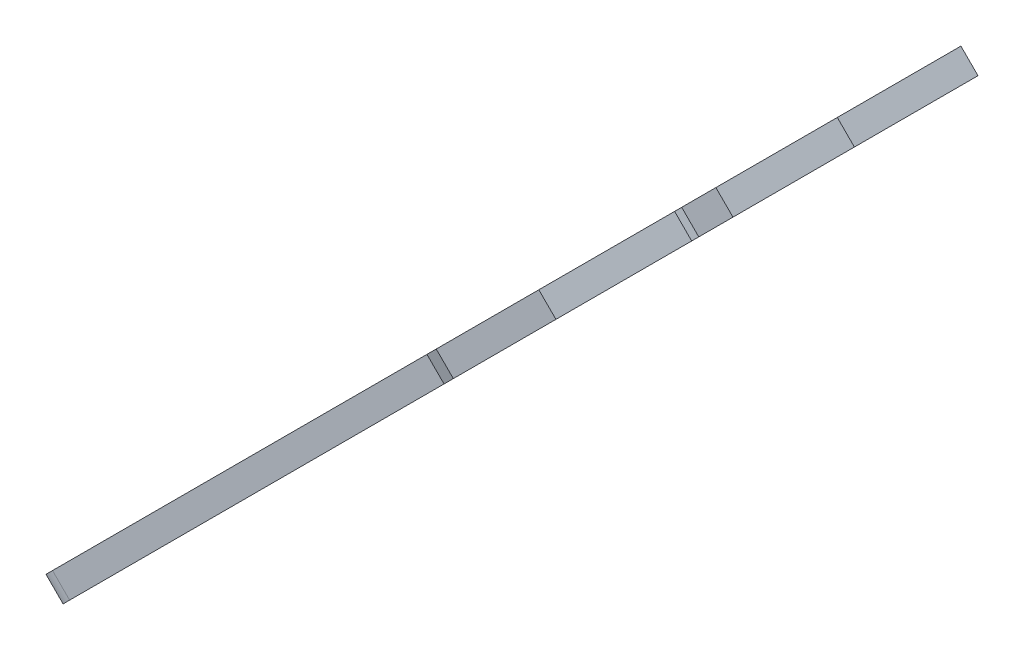
SolidWorks part; units mm, degrees
ref_plane "Front Plane" through (0, 0, 0) normal (0, 0, 1) x (1, 0, 0)
ref_plane "Top Plane" through (0, 0, 0) normal (0, 1, 0) x (1, 0, 0)
ref_plane "Right Plane" through (0, 0, 0) normal (1, 0, 0) x (0, 0, -1)
sketch "Sketch1" plane through (0, 0, 0) normal (0, 0, 1) x (1, 0, 0)
  line L0 (-4.4901, -21.951) -> (0, -26.4411)
  line L1 (-4.4901, -21.951) -> (-143.9339, -161.3948)
  line L2 (0, -26.4411) -> (-139.4438, -165.8849)
  line L3 (-143.9339, -161.3948) -> (-139.4438, -165.8849)
  line L4 (-143.6841, -161.1449) -> (-136.1856, -153.6464) construction
  line L5 (0, -17.4608) -> (9.1823, -26.6431) construction
  arc A0 (-208.1777, -57.2265) -> (-143.6841, -161.1449) centre (0, 0) ccw construction
  dimension "D1" = 6.35
  dimension "D2" = 6.35
extrude "Base Extrusion" add sketch "Sketch1" against normal up to surface (88.9 mm away) and the other way offset from surface (15.5875 mm away) 12.7
sketch "Sketch2" plane through (0, 0, -88.9) normal (0, 0, -1) x (-1, 0, 0)
  line L0 (12.3479, -38.7889) -> (16.838, -34.2988)
  line L1 (12.3479, -38.7889) -> (23.5732, -50.0143)
  line L2 (16.838, -34.2988) -> (28.0633, -45.5241)
  line L3 (23.5732, -50.0143) -> (28.0633, -45.5241)
  line L4 (0, -26.4411) -> (139.4438, -165.8849) construction
  line L5 (48.2689, -2.8679) -> (12.3479, -38.7889) construction
  line L6 (143.9339, -161.3948) -> (4.4901, -21.951) construction
  line L7 (59.4942, -14.0932) -> (23.5732, -50.0143) construction
extrude "Picker Clearance" cut sketch "Sketch2" against normal offset from surface (98.425 mm away) 9.525
sketch "Sketch3" plane through (13.2205, -13.2205, 0) normal (0.7071, -0.7071, 0) x (0, 0, -1)
  line L0 (88.9, -215.9) -> (-15.5875, -215.9) construction
  line L1 (54.2625, -203.2) -> (47.9125, -203.2)
  line L2 (54.2625, -203.2) -> (54.2625, -215.9)
  line L3 (54.2625, -215.9) -> (47.9125, -215.9)
  line L4 (47.9125, -203.2) -> (47.9125, -215.9)
  line L7 (-28.2875, 207.3747) -> (-28.2875, -207.3747) construction
  dimension "D1" = 12.7
  dimension "D2" = 76.2
  dimension "D3" = 6.35
extrude "Clothes Line Notch" cut sketch "Sketch3" against normal through all
sketch "Sketch4" plane through (0, 0, -88.9) normal (0, 0, -1) x (-1, 0, 0)
  line L0 (123.6156, -150.0567) -> (128.1057, -145.5666)
  line L1 (23.5732, -50.0143) -> (139.4438, -165.8849) construction
  line L2 (143.9339, -161.3948) -> (28.0633, -45.5241) construction
  line L3 (128.1057, -145.5666) -> (110.1452, -127.6061)
  line L4 (110.1452, -127.6061) -> (105.6551, -132.0962)
  line L5 (105.6551, -132.0962) -> (123.6156, -150.0567)
  dimension "D1" = 25.4
extrude "Tab to Top Plate" add sketch "Sketch4" along normal blind 6.35
pattern_linear "Top Plate Tabs" count 3 spacing 38.1 along (0.7071, 0.7071, 0) of "Tab to Top Plate"
sketch "Sketch5" plane through (8.7304, -8.7304, 0) normal (-0.7071, 0.7071, 0) x (0, 0, 1)
  line L1 (-6.35, -190.1467) -> (0, -190.1467)
  line L2 (-6.35, -190.1467) -> (-6.35, -164.7384)
  line L3 (-6.35, -164.7384) -> (0, -164.7384)
  line L4 (0, -190.1467) -> (0, -164.7384)
  dimension "D1" = 25.4083
  dimension "D2" = 6.35
extrude "Base Plate Tab" cut sketch "Sketch5" against normal blind 6.35
pattern_linear "Base Plate Tab holes" count 3 spacing 38.1 along (0.7071, 0.7071, 0) of "Base Plate Tab"
ref_plane "Plane1" through (-143.9339, -161.3948, -54.2625) normal (0, 0, 1) x (1, 0, 0)
sketch "Sketch8" plane through (8.7304, -8.7304, 0) normal (-0.7071, 0.7071, 0) x (0, 0, 1)
  line L0 (-88.9, -215.9) -> (-54.2625, -215.9) construction
  line L1 (-19.05, -209.55) -> (-6.35, -209.55)
  line L2 (-19.05, -209.55) -> (-19.05, -203.2)
  line L3 (-19.05, -203.2) -> (-6.35, -203.2)
  line L4 (-6.35, -209.55) -> (-6.35, -203.2)
  line L6 (15.5875, -18.6967) -> (15.5875, -215.9) construction
  dimension "D1" = 6.35
  dimension "D2" = 12.7
  dimension "D3" = 6.35
  dimension "D4" = 21.9375
extrude "Break Beam " cut sketch "Sketch8" against normal blind 6.35
pattern_linear "Break Beam Holes" count 2 spacing 19.05 along (0, 0, -1) of "Break Beam "
sketch "Sketch10" plane through (13.2205, -13.2205, 0) normal (0.7071, -0.7071, 0) x (0, 0, -1)
  line L0 (54.2625, -188.002) -> (47.9125, -192.2692) construction
  line L1 (47.9125, -188.002) -> (54.2625, -192.2692) construction
  circle A0 centre (51.0875, -190.1356) radius 2.0955
  dimension "D1" = 4.191
extrude "Clothes Line Hole" cut sketch "Sketch10" against normal through all
sketch "Sketch11" plane through (8.7304, -8.7304, 0) normal (-0.7071, 0.7071, 0) x (0.7071, 0.7071, 0)
  line L0 (-161.7656, 78.1771) -> (-161.7656, 120.5388) construction
  line L1 (-71.9749, 62.1718) -> (-71.9749, 114.782) construction
  line L2 (-27.4279, 73.0991) -> (-27.4279, 108.5444) construction
  line L5 (-52.0342, -9.525) -> (-52.0342, 88.9) construction
  line L6 (-91.9156, 95.25) -> (-91.9156, 88.9) construction
  line L7 (-36.1592, -9.525) -> (-36.1592, 88.9) construction
  line L8 (-18.6967, 88.9) -> (-18.6967, -15.5875) construction
  line L9 (-215.0889, 88.9) -> (-193.5156, 88.9) construction
  line L10 (-91.9156, 88.9) -> (-52.0342, 88.9) construction
  line L11 (-36.1592, 88.9) -> (-18.6967, 88.9) construction
  line L12 (-168.1156, 95.25) -> (-168.1156, 88.9) construction
  line L13 (-155.4156, 95.25) -> (-155.4156, 88.9) construction
  line B0 (-159.632, 88.9) -> (-163.8992, 88.9)
  line B1 (-163.8992, 76.962) -> (-166.2106, 76.962)
  line B2 (-166.2106, 76.962) -> (-166.2106, 80.137)
  line B3 (-166.2106, 80.137) -> (-163.8992, 80.137)
  line B4 (-163.8992, 80.137) -> (-163.8992, 88.9)
  line B5 (-163.8992, 76.962) -> (-163.8992, 73.66)
  line B6 (-163.8992, 73.66) -> (-159.632, 73.66)
  line B7 (-159.632, 76.962) -> (-159.632, 73.66)
  line B8 (-159.632, 80.137) -> (-159.632, 88.9)
  line B9 (-157.3206, 80.137) -> (-159.632, 80.137)
  line B10 (-157.3206, 76.962) -> (-157.3206, 80.137)
  line B11 (-159.632, 76.962) -> (-157.3206, 76.962)
  line B12 (-69.8413, 88.9) -> (-74.1085, 88.9)
  line B13 (-74.1085, 76.962) -> (-76.4199, 76.962)
  line B14 (-76.4199, 76.962) -> (-76.4199, 80.137)
  line B15 (-76.4199, 80.137) -> (-74.1085, 80.137)
  line B16 (-74.1085, 80.137) -> (-74.1085, 88.9)
  line B17 (-74.1085, 76.962) -> (-74.1085, 73.66)
  line B18 (-74.1085, 73.66) -> (-69.8413, 73.66)
  line B19 (-69.8413, 76.962) -> (-69.8413, 73.66)
  line B20 (-69.8413, 80.137) -> (-69.8413, 88.9)
  line B21 (-67.5299, 80.137) -> (-69.8413, 80.137)
  line B22 (-67.5299, 76.962) -> (-67.5299, 80.137)
  line B23 (-69.8413, 76.962) -> (-67.5299, 76.962)
  line B24 (-25.2943, 88.9) -> (-29.5615, 88.9)
  line B25 (-29.5615, 76.962) -> (-31.8729, 76.962)
  line B26 (-31.8729, 76.962) -> (-31.8729, 80.137)
  line B27 (-31.8729, 80.137) -> (-29.5615, 80.137)
  line B28 (-29.5615, 80.137) -> (-29.5615, 88.9)
  line B29 (-29.5615, 76.962) -> (-29.5615, 73.66)
  line B30 (-29.5615, 73.66) -> (-25.2943, 73.66)
  line B31 (-25.2943, 76.962) -> (-25.2943, 73.66)
  line B32 (-25.2943, 80.137) -> (-25.2943, 88.9)
  line B33 (-22.9829, 80.137) -> (-25.2943, 80.137)
  line B34 (-22.9829, 76.962) -> (-22.9829, 80.137)
  line B35 (-25.2943, 76.962) -> (-22.9829, 76.962)
sketch_block_instance "TSlot-1"
sketch_block "TSlot" parameters "D1"=3.302, "D2"=3.175
sketch_block_instance "TSlot-2"
sketch_block_instance "TSlot-3"
extrude "Chassis top Plate T Slot Hotes" cut sketch "Sketch11" against normal through all
sketch "Sketch12" plane through (8.7304, -8.7304, 0) normal (-0.7071, 0.7071, 0) x (0.7071, 0.7071, 0)
  line L0 (-204.9422, 0) -> (-200.7512, 6.35) construction
  line L1 (-200.7512, 0) -> (-204.9422, 6.35) construction
  line L2 (-209.55, 6.35) -> (-203.2, 6.35) construction
  line L3 (-204.9422, 0) -> (-204.9422, 6.35) construction
  line L4 (-72.3859, 0) -> (-68.1949, 6.35) construction
  line L5 (-68.1949, 0) -> (-72.3859, 6.35) construction
  line L6 (-29.5234, 0) -> (-25.3324, 6.35) construction
  line L7 (-25.3324, 0) -> (-29.5234, 6.35) construction
  circle A0 centre (-202.8467, 3.175) radius 2.0955
  circle A1 centre (-70.2904, 3.175) radius 2.0955
  circle A2 centre (-27.4279, 3.175) radius 2.0955
  dimension "D1" = 4.191
extrude "Chassis Base Plate Holes" cut sketch "Sketch12" against normal through all
fillet "V Funnel Corner Fillet" radius 7.62 1 edges at (-141.6889, -163.6398, 15.5875)
sketch "Sketch13" plane through (8.7304, -8.7304, 0) normal (-0.7071, 0.7071, 0) x (0, 0, 1)
  line L0 (15.5875, -18.6967) -> (15.5875, -208.28) construction
  line L2 (15.5875, -56.7967) -> (15.5875, -31.3967)
  line L4 (21.9375, -56.7967) -> (21.9375, -31.3967)
  line L5 (9.525, -44.0967) -> (15.5875, -44.0967) construction
  line L6 (9.525, -36.1592) -> (9.525, -52.0342) construction
  line L7 (21.9375, -56.7967) -> (15.5875, -69.228)
  line L8 (15.5875, -69.228) -> (15.5875, -56.7967)
  line L11 (21.9375, -31.3967) -> (21.9375, -18.6967)
  line L12 (21.9375, -18.6967) -> (15.5875, -18.6967)
  line L13 (15.5875, -31.3967) -> (15.5875, -18.6967)
  dimension "D1" = 25.4
  dimension "D2" = 6.35
extrude "Boss-Extrude1" add sketch "Sketch13" against normal blind 6.35
sketch "Sketch14" plane through (8.7304, -8.7304, 0) normal (-0.7071, 0.7071, 0) x (0, 0, 1)
  line L0 (9.525, -52.0342) -> (9.525, -36.1592)
  line L2 (9.525, -52.0342) -> (15.875, -52.0342)
  line L4 (9.525, -36.1592) -> (15.875, -36.1592)
  line L5 (15.875, -52.0342) -> (15.875, -36.1592)
  dimension "D1" = 6.35
extrude "Cut-Extrude1" cut sketch "Sketch14" against normal through all
sketch "Sketch16" plane through (-13.2205, -13.2205, 0) normal (0.7071, 0.7071, 0) x (0, 0, -1)
  line L0 (-21.9375, -18.6967) -> (15.0083, -18.6967) construction
  line L1 (88.9, -18.6967) -> (-21.9375, -18.6967) construction
  line L2 (15.0083, -18.6967) -> (51.9542, -18.6967) construction
  line L3 (51.9542, -18.6967) -> (88.9, -18.6967) construction
  line L4 (88.9, -12.3467) -> (-21.9375, -12.3467) construction
  line L5 (15.0083, -18.6967) -> (51.9542, -18.6967)
  line L6 (15.0083, -18.6967) -> (15.0083, -12.3467)
  line L7 (15.0083, -12.3467) -> (51.9542, -12.3467)
  line L8 (51.9542, -18.6967) -> (51.9542, -12.3467)
extrude "Boss-Extrude2" add sketch "Sketch16" along normal blind 6.35
sketch "Sketch17" [suppressed] plane through (-13.2205, -13.2205, 0) normal (0.7071, 0.7071, 0) x (0, 0, -1)
  line L0 (-21.9375, -18.6967) -> (15.0083, -18.6967) construction
  line L1 (88.9, -18.6967) -> (-21.9375, -18.6967) construction
  line L2 (15.0083, -18.6967) -> (51.9542, -18.6967) construction
  line L3 (51.9542, -18.6967) -> (88.9, -18.6967) construction
  line L4 (88.9, -12.3467) -> (-21.9375, -12.3467) construction
  line L5 (-21.9375, -18.6967) -> (15.0083, -18.6967)
  line L6 (-21.9375, -18.6967) -> (-21.9375, -12.3467)
  line L7 (-21.9375, -12.3467) -> (15.0083, -12.3467)
  line L8 (15.0083, -18.6967) -> (15.0083, -12.3467)
  line L10 (51.9542, -18.6967) -> (88.9, -18.6967)
  line L11 (51.9542, -18.6967) -> (51.9542, -12.3467)
  line L12 (51.9542, -12.3467) -> (88.9, -12.3467)
  line L13 (88.9, -18.6967) -> (88.9, -12.3467)
extrude "Boss-Extrude3" [suppressed] add sketch "Sketch17" along normal blind 6.35
sketch "Sketch18" plane through (8.7304, -8.7304, 0) normal (-0.7071, 0.7071, 0) x (0.7071, 0.7071, 0)
  line L0 (-204.8136, 78.3336) -> (-144.155, 78.3336) construction
  line L1 (-209.55, 82.55) -> (-180.086, 82.55)
  line L2 (-209.55, 82.55) -> (-209.55, 74.1172)
  line L3 (-209.55, 74.1172) -> (-180.086, 74.1172)
  line L4 (-180.086, 82.55) -> (-180.086, 74.1172)
  line L7 (-215.9, 88.9) -> (-193.5156, 88.9) construction
  line L8 (-215.9, 88.9) -> (-215.9, 54.2625) construction
  dimension "D1" = 29.464
  dimension "D2" = 8.4328
  dimension "D3" = 6.35
  dimension "D4" = 6.35
extrude "Cut-Extrude2" cut sketch "Sketch18" against normal through all
sketch "Sketch19" plane through (8.7304, -8.7304, 0) normal (-0.7071, 0.7071, 0) x (0.7071, 0.7071, 0)
  line L0 (-12.3467, 51.9542) -> (-12.3467, 15.0083) construction
  line L1 (-25.0467, 13.716) -> (-12.3467, 13.716)
  line L2 (-25.0467, 13.716) -> (-25.0467, 20.066)
  line L3 (-25.0467, 20.066) -> (-12.3467, 20.066)
  line L4 (-12.3467, 13.716) -> (-12.3467, 20.066)
  line L5 (-25.8391, 16.891) -> (-12.3467, 16.891) construction
  line L6 (-25.3324, 6.35) -> (-12.3467, 6.35) construction
  dimension "D1" = 10.541
  dimension "D2" = 6.35
  dimension "D3" = 12.7
extrude "Cut-Extrude3" cut sketch "Sketch19" against normal through all
sketch "Sketch20" [suppressed] plane through (13.2205, -13.2205, 0) normal (0.7071, -0.7071, 0) x (0, 0, -1)
  line L0 (-21.9375, -12.3467) -> (15.0083, -12.3467) construction
  line L1 (13.716, -25.0467) -> (20.066, -25.0467)
  line L2 (13.716, -25.0467) -> (13.716, -12.3467)
  line L3 (13.716, -12.3467) -> (20.066, -12.3467)
  line L4 (20.066, -25.0467) -> (20.066, -12.3467)
  line L5 (16.891, -25.0467) -> (16.891, -11.7014) construction
  line L6 (6.35, -12.3467) -> (6.35, -25.3324) construction
  dimension "D1" = 10.541
  dimension "D2" = 6.35
  dimension "D3" = 12.7
extrude "Cut-Extrude4" [suppressed] cut sketch "Sketch20" against normal through all
sketch "Sketch21" [suppressed] plane through (8.7304, -8.7304, 0) normal (-0.7071, 0.7071, 0) x (0, 0, 1)
  line L1 (3.5175, -29.4467) -> (9.2375, -29.4467)
  line L2 (3.5175, -29.4467) -> (3.5175, -25.0467)
  line L3 (3.5175, -25.0467) -> (9.2375, -25.0467)
  line L4 (9.2375, -29.4467) -> (9.2375, -25.0467)
extrude "Cut-Extrude5" [suppressed] cut sketch "Sketch21" against normal through all
sketch "Sketch22" plane through (13.2205, -13.2205, 0) normal (0.7071, -0.7071, 0) x (0, 0, -1)
  line L1 (-3.5175, -25.0467) -> (-9.2375, -25.0467)
  line L2 (-3.5175, -25.0467) -> (-3.5175, -29.4467)
  line L3 (-3.5175, -29.4467) -> (-9.2375, -29.4467)
  line L4 (-9.2375, -25.0467) -> (-9.2375, -29.4467)
extrude "Cut-Extrude6" cut sketch "Sketch22" against normal through all
